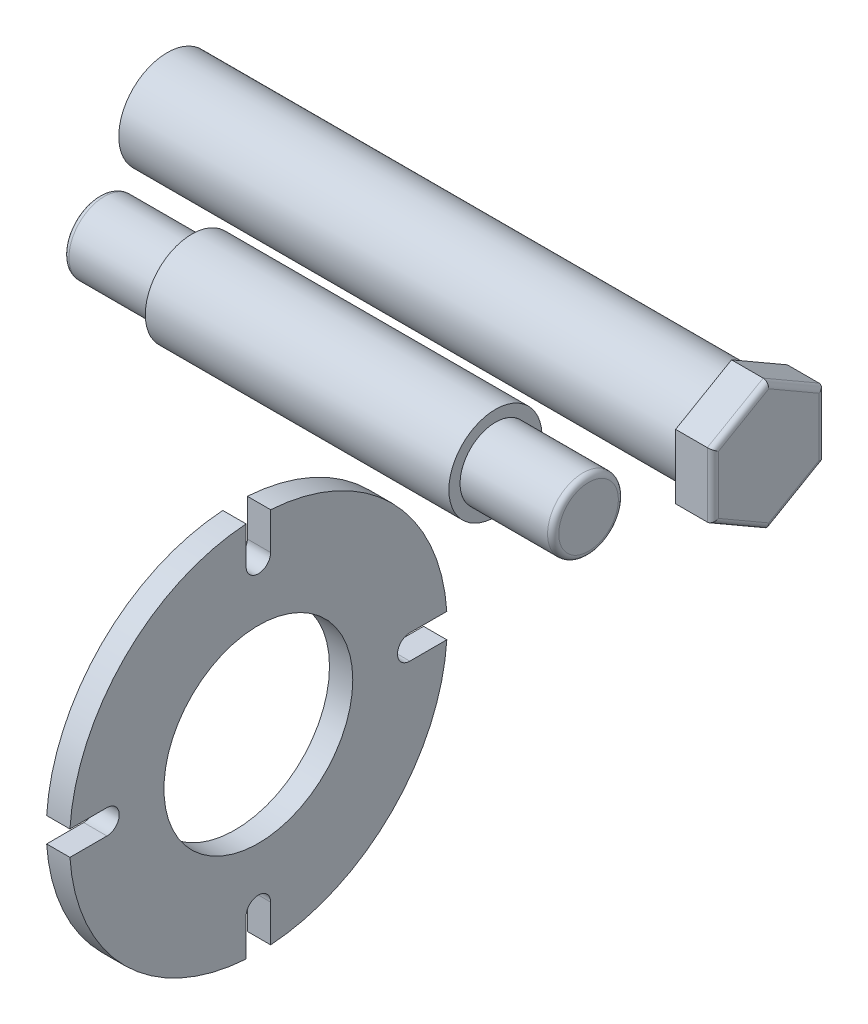
SolidWorks part; units mm, degrees
ref_plane "Front Plane" through (0, 0, 0) normal (0, 0, 1) x (1, 0, 0)
ref_plane "Top Plane" through (0, 0, 0) normal (0, 1, 0) x (1, 0, 0)
ref_plane "Right Plane" through (0, 0, 0) normal (1, 0, 0) x (0, 0, -1)
sketch "Sketch2" plane through (0, 0, 0) normal (1, 0, 0) x (0, 0, -1)
  line L0 (0, 31.8055) -> (0, -40.3146) construction
  line L1 (-37.3571, 0) -> (35.5931, 0) construction
  line L2 (20.6502, 1.674) -> (25.699, 1.674)
  line L3 (20.6502, -1.674) -> (25.699, -1.674)
  line L4 (1.674, -20.6502) -> (1.674, -25.699)
  line L5 (-1.674, -20.6502) -> (-1.674, -25.699)
  line L6 (-20.6502, -1.674) -> (-25.699, -1.674)
  line L7 (-20.6502, 1.674) -> (-25.699, 1.674)
  line L8 (-1.674, 20.6502) -> (-1.674, 25.699)
  line L9 (1.674, 20.6502) -> (1.674, 25.699)
  arc A0 (25.699, 1.674) -> (1.674, 25.699) centre (0, 0) ccw
  circle A1 centre (0, 0) radius 12.8767
  arc A2 (20.6502, 1.674) -> (20.6502, -1.674) centre (20.6502, 0) ccw
  arc A3 (1.674, -20.6502) -> (-1.674, -20.6502) centre (0, -20.6502) ccw
  arc A4 (-20.6502, -1.674) -> (-20.6502, 1.674) centre (-20.6502, 0) ccw
  arc A5 (-1.674, 20.6502) -> (1.674, 20.6502) centre (0, 20.6502) ccw
  arc A6 (-1.674, 25.699) -> (-25.699, 1.674) centre (0, 0) ccw
  arc A7 (-25.699, -1.674) -> (-1.674, -25.699) centre (0, 0) ccw
  arc A8 (1.674, -25.699) -> (25.699, -1.674) centre (0, 0) ccw
  point P30 (0, 0)
  dimension "D1" = 20.6502
  dimension "D2" = 4
extrude "Boss-Extrude1" add sketch "Sketch2" along normal blind 3.175
sketch "Sketch3" plane through (0, 0, 0) normal (1, 0, 0) x (0, 0, -1)
  circle A0 centre (48.2087, 0) radius 4.826
extrude "Boss-Extrude2" add sketch "Sketch3" against normal blind 12.7 separate body
sketch "Sketch4" plane through (-12.7, 0, 0) normal (-1, 0, 0) x (0, 0, 1)
  circle A0 centre (-48.2087, 0) radius 6.35
  circle A1 centre (-48.2087, 0) radius 4.826
  circle A2 centre (-48.2087, 0) radius 4.826
  dimension "D1" = 0
extrude "Boss-Extrude3" add sketch "Sketch4" along normal blind 41.402 separate body contours A2 | A0
sketch "Sketch5" plane through (-54.102, 0, 0) normal (-1, 0, 0) x (0, 0, 1)
  circle A0 centre (-48.2087, 0) radius 4.826 construction
  circle A1 centre (-48.2087, 0) radius 4.826
extrude "Boss-Extrude4" add sketch "Sketch5" along normal blind 12.7 separate body
sketch "Sketch7" plane through (0, 0, 0) normal (1, 0, 0) x (0, 0, -1)
  circle A0 centre (67.7025, 0) radius 6.604
extrude "Boss-Extrude5" add sketch "Sketch7" against normal blind 76.962 separate body
sketch "Sketch8" plane through (0, 0, 0) normal (1, 0, 0) x (0, 0, -1)
  line L1 (67.7025, -8.7988) -> (75.3225, -4.3994)
  line L2 (75.3225, -4.3994) -> (75.3225, 4.3994)
  line L3 (75.3225, 4.3994) -> (67.7025, 8.7988)
  line L4 (67.7025, 8.7988) -> (60.0825, 4.3994)
  line L5 (60.0825, 4.3994) -> (60.0825, -4.3994)
  line L6 (60.0825, -4.3994) -> (67.7025, -8.7988)
  circle A0 centre (67.7025, 0) radius 7.62 construction
  dimension "D1" = 15.24
extrude "Boss-Extrude6" add sketch "Sketch8" along normal blind 5.08
fillet "Fillet1" radius 0.762 1 edges at (0, 0, -53.0347)
fillet "Fillet2" radius 0.762 1 edges at (-66.802, 0, -43.3827)
fillet "Fillet3" radius 0.762 6 edges at (5.08, 0, -60.0825) (5.08, 6.5991, -63.8925) (5.08, 6.5991, -71.5125) (5.08, 0, -75.3225) (5.08, -6.5991, -71.5125) (5.08, -6.5991, -63.8925)
